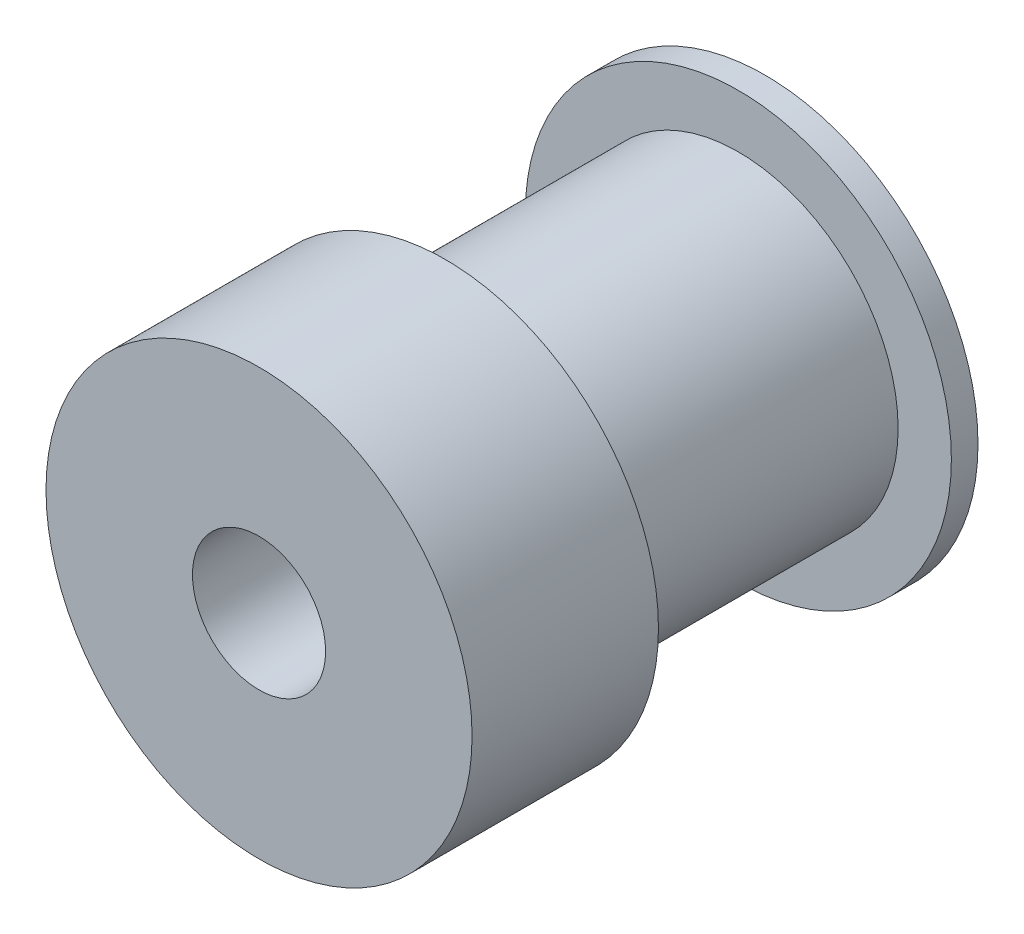
SolidWorks part; units mm, degrees
ref_plane "前视基准面" through (0, 0, 0) normal (0, 0, 1) x (1, 0, 0)
ref_plane "上视基准面" through (0, 0, 0) normal (0, 1, 0) x (1, 0, 0)
ref_plane "右视基准面" through (0, 0, 0) normal (1, 0, 0) x (0, 0, -1)
other "Configuration Table"
sketch "草图1" plane through (0, 0, 0) normal (0, 0, 1) x (1, 0, 0)
  circle A0 centre (0, 0) radius 8
  dimension "D1" = 16
extrude "凸台-拉伸1" add sketch "草图1" along normal blind 19
sketch "草图2" plane through (0, 0, 19) normal (0, 0, 1) x (1, 0, 0)
  circle A0 centre (0, 0) radius 6
  circle A1 centre (0, 0) radius 8
  dimension "D1" = 12
extrude "切除-拉伸3" cut sketch "草图2" against normal blind 11 from offset 7 contours A1 | A0 offset against normal yes
sketch "草图3" plane through (0, 0, 19) normal (0, 0, 1) x (1, 0, 0)
  circle A0 centre (0, 0) radius 2.5
  dimension "D1" = 5
extrude "切除-拉伸4" cut sketch "草图3" against normal through all
